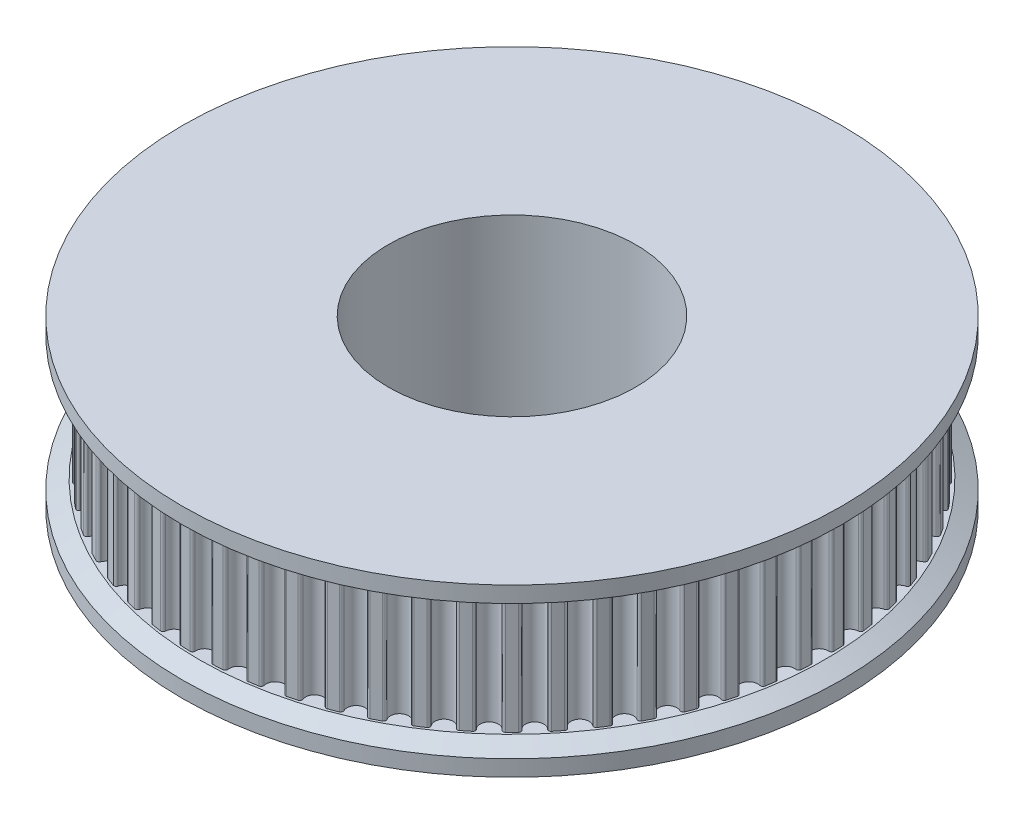
SolidWorks part; units mm, degrees
material "1060 Сплав"
ref_plane "Спереди" through (0, 0, 0) normal (0, 0, 1) x (1, 0, 0)
ref_plane "Сверху" through (0, 0, 0) normal (0, 1, 0) x (1, 0, 0)
ref_plane "Справа" through (0, 0, 0) normal (1, 0, 0) x (0, 0, -1)
other "Configuration Table"
sketch "Эскиз1" plane through (0, 0, 0) normal (0, 1, 0) x (1, 0, 0)
  circle A0 centre (0, 0) radius 10
  circle A1 centre (0, 0) radius 7.5
  dimension "D1" = 20
  dimension "D2" = 15
extrude "Бобышка-Вытянуть1" add sketch "Эскиз1" along normal blind 7.45
sketch "Эскиз2" plane through (0, 7.45, 0) normal (0, 1, 0) x (1, 0, 0)
  arc A1 (1.2682, 18.8073) -> (0.7046, 18.8368) centre (0, 0) ccw
  arc A3 (-0.5492, 18.679) -> (0.5492, 18.679) centre (0, 18.65) ccw
  arc A74 (-0.5492, 18.679) -> (-0.7046, 18.8368) centre (-0.699, 18.6869) ccw
  arc A77 (0.5492, 18.679) -> (0.7046, 18.8368) centre (0.699, 18.6869) cw
  arc A82 (-0.7046, 18.8368) -> (-1.2682, 18.8073) centre (0, 0) ccw
  arc A83 (1.4063, 18.6341) -> (2.4987, 18.5193) centre (1.9495, 18.5478) ccw
  arc A84 (1.4063, 18.6341) -> (1.2682, 18.8073) centre (1.2581, 18.6576) ccw
  arc A85 (2.4987, 18.5193) -> (2.6698, 18.66) centre (2.6485, 18.5115) cw
  arc A86 (3.3464, 18.385) -> (4.4208, 18.1566) centre (3.8776, 18.2425) ccw
  arc A87 (3.3464, 18.385) -> (3.2272, 18.5717) centre (3.2015, 18.4239) ccw
  arc A88 (4.4208, 18.1566) -> (4.6056, 18.2787) centre (4.569, 18.1332) cw
  arc A89 (5.2498, 17.9345) -> (6.2945, 17.5951) centre (5.7632, 17.7372) ccw
  arc A90 (5.2498, 17.9345) -> (5.1508, 18.1326) centre (5.1098, 17.9883) ccw
  arc A91 (6.2945, 17.5951) -> (6.491, 17.6971) centre (6.4394, 17.5563) cw
  arc A92 (7.0957, 17.2875) -> (8.0992, 16.8407) centre (7.5856, 17.0376) ccw
  arc A93 (7.0957, 17.2875) -> (7.0179, 17.4949) centre (6.9621, 17.3557) ccw
  arc A94 (8.0992, 16.8407) -> (8.3053, 16.9217) centre (8.2393, 16.787) cw
  arc A95 (8.8639, 16.4511) -> (9.8152, 15.9019) centre (9.325, 16.1514) ccw
  arc A96 (8.8639, 16.4511) -> (8.8082, 16.6655) centre (8.7381, 16.5329) ccw
  arc A97 (9.8152, 15.9019) -> (10.0286, 15.9609) centre (9.9488, 15.8338) cw
  arc A98 (10.5349, 15.4345) -> (11.4236, 14.7888) centre (10.9622, 15.0882) ccw
  arc A99 (10.5349, 15.4345) -> (10.5019, 15.6535) centre (10.4184, 15.5289) ccw
  arc A100 (11.4236, 14.7888) -> (11.6421, 14.8251) centre (11.5494, 14.7072) cw
  arc A101 (12.0905, 14.2487) -> (12.9069, 13.5137) centre (12.4793, 13.8597) ccw
  arc A102 (12.0905, 14.2487) -> (12.0807, 14.47) centre (11.9845, 14.3548) ccw
  arc A103 (12.9069, 13.5137) -> (13.1279, 13.527) centre (13.0235, 13.4194) cw
  arc A104 (13.5137, 12.9069) -> (14.2487, 12.0905) centre (13.8597, 12.4793) ccw
  arc A105 (13.5137, 12.9069) -> (13.527, 13.1279) centre (13.4194, 13.0235) ccw
  arc A106 (14.2487, 12.0905) -> (14.47, 12.0807) centre (14.3548, 11.9845) cw
  arc A107 (14.7888, 11.4236) -> (15.4345, 10.5349) centre (15.0882, 10.9622) ccw
  arc A108 (14.7888, 11.4236) -> (14.8251, 11.6421) centre (14.7072, 11.5494) ccw
  arc A109 (15.4345, 10.5349) -> (15.6535, 10.5019) centre (15.5289, 10.4184) cw
  arc A110 (15.9019, 9.8152) -> (16.4511, 8.8639) centre (16.1514, 9.325) ccw
  arc A111 (15.9019, 9.8152) -> (15.9609, 10.0286) centre (15.8338, 9.9488) ccw
  arc A112 (16.4511, 8.8639) -> (16.6655, 8.8082) centre (16.5329, 8.7381) cw
  arc A113 (16.8407, 8.0992) -> (17.2875, 7.0957) centre (17.0376, 7.5856) ccw
  arc A114 (16.8407, 8.0992) -> (16.9217, 8.3053) centre (16.787, 8.2393) ccw
  arc A115 (17.2875, 7.0957) -> (17.4949, 7.0179) centre (17.3557, 6.9621) cw
  arc A116 (17.5951, 6.2945) -> (17.9345, 5.2498) centre (17.7372, 5.7632) ccw
  arc A117 (17.5951, 6.2945) -> (17.6971, 6.491) centre (17.5563, 6.4394) ccw
  arc A118 (17.9345, 5.2498) -> (18.1326, 5.1508) centre (17.9883, 5.1098) cw
  arc A119 (18.1566, 4.4208) -> (18.385, 3.3464) centre (18.2425, 3.8776) ccw
  arc A120 (18.1566, 4.4208) -> (18.2787, 4.6056) centre (18.1332, 4.569) ccw
  arc A121 (18.385, 3.3464) -> (18.5717, 3.2272) centre (18.4239, 3.2015) cw
  arc A122 (18.5193, 2.4987) -> (18.6341, 1.4063) centre (18.5478, 1.9495) ccw
  arc A123 (18.5193, 2.4987) -> (18.66, 2.6698) centre (18.5115, 2.6485) ccw
  arc A124 (18.6341, 1.4063) -> (18.8073, 1.2682) centre (18.6576, 1.2581) cw
  arc A125 (18.679, 0.5492) -> (18.679, -0.5492) centre (18.65, 0) ccw
  arc A126 (18.679, 0.5492) -> (18.8368, 0.7046) centre (18.6869, 0.699) ccw
  arc A127 (18.679, -0.5492) -> (18.8368, -0.7046) centre (18.6869, -0.699) cw
  arc A128 (18.6341, -1.4063) -> (18.5193, -2.4987) centre (18.5478, -1.9495) ccw
  arc A129 (18.6341, -1.4063) -> (18.8073, -1.2682) centre (18.6576, -1.2581) ccw
  arc A130 (18.5193, -2.4987) -> (18.66, -2.6698) centre (18.5115, -2.6485) cw
  arc A131 (18.385, -3.3464) -> (18.1566, -4.4208) centre (18.2425, -3.8776) ccw
  arc A132 (18.385, -3.3464) -> (18.5717, -3.2272) centre (18.4239, -3.2015) ccw
  arc A133 (18.1566, -4.4208) -> (18.2787, -4.6056) centre (18.1332, -4.569) cw
  arc A134 (17.9345, -5.2498) -> (17.5951, -6.2945) centre (17.7372, -5.7632) ccw
  arc A135 (17.9345, -5.2498) -> (18.1326, -5.1508) centre (17.9883, -5.1098) ccw
  arc A136 (17.5951, -6.2945) -> (17.6971, -6.491) centre (17.5563, -6.4394) cw
  arc A137 (17.2875, -7.0957) -> (16.8407, -8.0992) centre (17.0376, -7.5856) ccw
  arc A138 (17.2875, -7.0957) -> (17.4949, -7.0179) centre (17.3557, -6.9621) ccw
  arc A139 (16.8407, -8.0992) -> (16.9217, -8.3053) centre (16.787, -8.2393) cw
  arc A140 (16.4511, -8.8639) -> (15.9019, -9.8152) centre (16.1514, -9.325) ccw
  arc A141 (16.4511, -8.8639) -> (16.6655, -8.8082) centre (16.5329, -8.7381) ccw
  arc A142 (15.9019, -9.8152) -> (15.9609, -10.0286) centre (15.8338, -9.9488) cw
  arc A143 (15.4345, -10.5349) -> (14.7888, -11.4236) centre (15.0882, -10.9622) ccw
  arc A144 (15.4345, -10.5349) -> (15.6535, -10.5019) centre (15.5289, -10.4184) ccw
  arc A145 (14.7888, -11.4236) -> (14.8251, -11.6421) centre (14.7072, -11.5494) cw
  arc A146 (14.2487, -12.0905) -> (13.5137, -12.9069) centre (13.8597, -12.4793) ccw
  arc A147 (14.2487, -12.0905) -> (14.47, -12.0807) centre (14.3548, -11.9845) ccw
  arc A148 (13.5137, -12.9069) -> (13.527, -13.1279) centre (13.4194, -13.0235) cw
  arc A149 (12.9069, -13.5137) -> (12.0905, -14.2487) centre (12.4793, -13.8597) ccw
  arc A150 (12.9069, -13.5137) -> (13.1279, -13.527) centre (13.0235, -13.4194) ccw
  arc A151 (12.0905, -14.2487) -> (12.0807, -14.47) centre (11.9845, -14.3548) cw
  arc A152 (11.4236, -14.7888) -> (10.5349, -15.4345) centre (10.9622, -15.0882) ccw
  arc A153 (11.4236, -14.7888) -> (11.6421, -14.8251) centre (11.5494, -14.7072) ccw
  arc A154 (10.5349, -15.4345) -> (10.5019, -15.6535) centre (10.4184, -15.5289) cw
  arc A155 (9.8152, -15.9019) -> (8.8639, -16.4511) centre (9.325, -16.1514) ccw
  arc A156 (9.8152, -15.9019) -> (10.0286, -15.9609) centre (9.9488, -15.8338) ccw
  arc A157 (8.8639, -16.4511) -> (8.8082, -16.6655) centre (8.7381, -16.5329) cw
  arc A158 (8.0992, -16.8407) -> (7.0957, -17.2875) centre (7.5856, -17.0376) ccw
  arc A159 (8.0992, -16.8407) -> (8.3053, -16.9217) centre (8.2393, -16.787) ccw
  arc A160 (7.0957, -17.2875) -> (7.0179, -17.4949) centre (6.9621, -17.3557) cw
  arc A161 (6.2945, -17.5951) -> (5.2498, -17.9345) centre (5.7632, -17.7372) ccw
  arc A162 (6.2945, -17.5951) -> (6.491, -17.6971) centre (6.4394, -17.5563) ccw
  arc A163 (5.2498, -17.9345) -> (5.1508, -18.1326) centre (5.1098, -17.9883) cw
  arc A164 (4.4208, -18.1566) -> (3.3464, -18.385) centre (3.8776, -18.2425) ccw
  arc A165 (4.4208, -18.1566) -> (4.6056, -18.2787) centre (4.569, -18.1332) ccw
  arc A166 (3.3464, -18.385) -> (3.2272, -18.5717) centre (3.2015, -18.4239) cw
  arc A167 (2.4987, -18.5193) -> (1.4063, -18.6341) centre (1.9495, -18.5478) ccw
  arc A168 (2.4987, -18.5193) -> (2.6698, -18.66) centre (2.6485, -18.5115) ccw
  arc A169 (1.4063, -18.6341) -> (1.2682, -18.8073) centre (1.2581, -18.6576) cw
  arc A170 (0.5492, -18.679) -> (-0.5492, -18.679) centre (0, -18.65) ccw
  arc A171 (0.5492, -18.679) -> (0.7046, -18.8368) centre (0.699, -18.6869) ccw
  arc A172 (-0.5492, -18.679) -> (-0.7046, -18.8368) centre (-0.699, -18.6869) cw
  arc A173 (-1.4063, -18.6341) -> (-2.4987, -18.5193) centre (-1.9495, -18.5478) ccw
  arc A174 (-1.4063, -18.6341) -> (-1.2682, -18.8073) centre (-1.2581, -18.6576) ccw
  arc A175 (-2.4987, -18.5193) -> (-2.6698, -18.66) centre (-2.6485, -18.5115) cw
  arc A176 (-3.3464, -18.385) -> (-4.4208, -18.1566) centre (-3.8776, -18.2425) ccw
  arc A177 (-3.3464, -18.385) -> (-3.2272, -18.5717) centre (-3.2015, -18.4239) ccw
  arc A178 (-4.4208, -18.1566) -> (-4.6056, -18.2787) centre (-4.569, -18.1332) cw
  arc A179 (-5.2498, -17.9345) -> (-6.2945, -17.5951) centre (-5.7632, -17.7372) ccw
  arc A180 (-5.2498, -17.9345) -> (-5.1508, -18.1326) centre (-5.1098, -17.9883) ccw
  arc A181 (-6.2945, -17.5951) -> (-6.491, -17.6971) centre (-6.4394, -17.5563) cw
  arc A182 (-7.0957, -17.2875) -> (-8.0992, -16.8407) centre (-7.5856, -17.0376) ccw
  arc A183 (-7.0957, -17.2875) -> (-7.0179, -17.4949) centre (-6.9621, -17.3557) ccw
  arc A184 (-8.0992, -16.8407) -> (-8.3053, -16.9217) centre (-8.2393, -16.787) cw
  arc A185 (-8.8639, -16.4511) -> (-9.8152, -15.9019) centre (-9.325, -16.1514) ccw
  arc A186 (-8.8639, -16.4511) -> (-8.8082, -16.6655) centre (-8.7381, -16.5329) ccw
  arc A187 (-9.8152, -15.9019) -> (-10.0286, -15.9609) centre (-9.9488, -15.8338) cw
  arc A188 (-10.5349, -15.4345) -> (-11.4236, -14.7888) centre (-10.9622, -15.0882) ccw
  arc A189 (-10.5349, -15.4345) -> (-10.5019, -15.6535) centre (-10.4184, -15.5289) ccw
  arc A190 (-11.4236, -14.7888) -> (-11.6421, -14.8251) centre (-11.5494, -14.7072) cw
  arc A191 (-12.0905, -14.2487) -> (-12.9069, -13.5137) centre (-12.4793, -13.8597) ccw
  arc A192 (-12.0905, -14.2487) -> (-12.0807, -14.47) centre (-11.9845, -14.3548) ccw
  arc A193 (-12.9069, -13.5137) -> (-13.1279, -13.527) centre (-13.0235, -13.4194) cw
  arc A194 (-13.5137, -12.9069) -> (-14.2487, -12.0905) centre (-13.8597, -12.4793) ccw
  arc A195 (-13.5137, -12.9069) -> (-13.527, -13.1279) centre (-13.4194, -13.0235) ccw
  arc A196 (-14.2487, -12.0905) -> (-14.47, -12.0807) centre (-14.3548, -11.9845) cw
  arc A197 (-14.7888, -11.4236) -> (-15.4345, -10.5349) centre (-15.0882, -10.9622) ccw
  arc A198 (-14.7888, -11.4236) -> (-14.8251, -11.6421) centre (-14.7072, -11.5494) ccw
  arc A199 (-15.4345, -10.5349) -> (-15.6535, -10.5019) centre (-15.5289, -10.4184) cw
  arc A200 (-15.9019, -9.8152) -> (-16.4511, -8.8639) centre (-16.1514, -9.325) ccw
  arc A201 (-15.9019, -9.8152) -> (-15.9609, -10.0286) centre (-15.8338, -9.9488) ccw
  arc A202 (-16.4511, -8.8639) -> (-16.6655, -8.8082) centre (-16.5329, -8.7381) cw
  arc A203 (-16.8407, -8.0992) -> (-17.2875, -7.0957) centre (-17.0376, -7.5856) ccw
  arc A204 (-16.8407, -8.0992) -> (-16.9217, -8.3053) centre (-16.787, -8.2393) ccw
  arc A205 (-17.2875, -7.0957) -> (-17.4949, -7.0179) centre (-17.3557, -6.9621) cw
  arc A206 (-17.5951, -6.2945) -> (-17.9345, -5.2498) centre (-17.7372, -5.7632) ccw
  arc A207 (-17.5951, -6.2945) -> (-17.6971, -6.491) centre (-17.5563, -6.4394) ccw
  arc A208 (-17.9345, -5.2498) -> (-18.1326, -5.1508) centre (-17.9883, -5.1098) cw
  arc A209 (-18.1566, -4.4208) -> (-18.385, -3.3464) centre (-18.2425, -3.8776) ccw
  arc A210 (-18.1566, -4.4208) -> (-18.2787, -4.6056) centre (-18.1332, -4.569) ccw
  arc A211 (-18.385, -3.3464) -> (-18.5717, -3.2272) centre (-18.4239, -3.2015) cw
  arc A212 (-18.5193, -2.4987) -> (-18.6341, -1.4063) centre (-18.5478, -1.9495) ccw
  arc A213 (-18.5193, -2.4987) -> (-18.66, -2.6698) centre (-18.5115, -2.6485) ccw
  arc A214 (-18.6341, -1.4063) -> (-18.8073, -1.2682) centre (-18.6576, -1.2581) cw
  arc A215 (-18.679, -0.5492) -> (-18.679, 0.5492) centre (-18.65, 0) ccw
  arc A216 (-18.679, -0.5492) -> (-18.8368, -0.7046) centre (-18.6869, -0.699) ccw
  arc A217 (-18.679, 0.5492) -> (-18.8368, 0.7046) centre (-18.6869, 0.699) cw
  arc A218 (-18.6341, 1.4063) -> (-18.5193, 2.4987) centre (-18.5478, 1.9495) ccw
  arc A219 (-18.6341, 1.4063) -> (-18.8073, 1.2682) centre (-18.6576, 1.2581) ccw
  arc A220 (-18.5193, 2.4987) -> (-18.66, 2.6698) centre (-18.5115, 2.6485) cw
  arc A221 (-18.385, 3.3464) -> (-18.1566, 4.4208) centre (-18.2425, 3.8776) ccw
  arc A222 (-18.385, 3.3464) -> (-18.5717, 3.2272) centre (-18.4239, 3.2015) ccw
  arc A223 (-18.1566, 4.4208) -> (-18.2787, 4.6056) centre (-18.1332, 4.569) cw
  arc A224 (-17.9345, 5.2498) -> (-17.5951, 6.2945) centre (-17.7372, 5.7632) ccw
  arc A225 (-17.9345, 5.2498) -> (-18.1326, 5.1508) centre (-17.9883, 5.1098) ccw
  arc A226 (-17.5951, 6.2945) -> (-17.6971, 6.491) centre (-17.5563, 6.4394) cw
  arc A227 (-17.2875, 7.0957) -> (-16.8407, 8.0992) centre (-17.0376, 7.5856) ccw
  arc A228 (-17.2875, 7.0957) -> (-17.4949, 7.0179) centre (-17.3557, 6.9621) ccw
  arc A229 (-16.8407, 8.0992) -> (-16.9217, 8.3053) centre (-16.787, 8.2393) cw
  arc A230 (-16.4511, 8.8639) -> (-15.9019, 9.8152) centre (-16.1514, 9.325) ccw
  arc A231 (-16.4511, 8.8639) -> (-16.6655, 8.8082) centre (-16.5329, 8.7381) ccw
  arc A232 (-15.9019, 9.8152) -> (-15.9609, 10.0286) centre (-15.8338, 9.9488) cw
  arc A233 (-15.4345, 10.5349) -> (-14.7888, 11.4236) centre (-15.0882, 10.9622) ccw
  arc A234 (-15.4345, 10.5349) -> (-15.6535, 10.5019) centre (-15.5289, 10.4184) ccw
  arc A235 (-14.7888, 11.4236) -> (-14.8251, 11.6421) centre (-14.7072, 11.5494) cw
  arc A236 (-14.2487, 12.0905) -> (-13.5137, 12.9069) centre (-13.8597, 12.4793) ccw
  arc A237 (-14.2487, 12.0905) -> (-14.47, 12.0807) centre (-14.3548, 11.9845) ccw
  arc A238 (-13.5137, 12.9069) -> (-13.527, 13.1279) centre (-13.4194, 13.0235) cw
  arc A239 (-12.9069, 13.5137) -> (-12.0905, 14.2487) centre (-12.4793, 13.8597) ccw
  arc A240 (-12.9069, 13.5137) -> (-13.1279, 13.527) centre (-13.0235, 13.4194) ccw
  arc A241 (-12.0905, 14.2487) -> (-12.0807, 14.47) centre (-11.9845, 14.3548) cw
  arc A242 (-11.4236, 14.7888) -> (-10.5349, 15.4345) centre (-10.9622, 15.0882) ccw
  arc A243 (-11.4236, 14.7888) -> (-11.6421, 14.8251) centre (-11.5494, 14.7072) ccw
  arc A244 (-10.5349, 15.4345) -> (-10.5019, 15.6535) centre (-10.4184, 15.5289) cw
  arc A245 (-9.8152, 15.9019) -> (-8.8639, 16.4511) centre (-9.325, 16.1514) ccw
  arc A246 (-9.8152, 15.9019) -> (-10.0286, 15.9609) centre (-9.9488, 15.8338) ccw
  arc A247 (-8.8639, 16.4511) -> (-8.8082, 16.6655) centre (-8.7381, 16.5329) cw
  arc A248 (-8.0992, 16.8407) -> (-7.0957, 17.2875) centre (-7.5856, 17.0376) ccw
  arc A249 (-8.0992, 16.8407) -> (-8.3053, 16.9217) centre (-8.2393, 16.787) ccw
  arc A250 (-7.0957, 17.2875) -> (-7.0179, 17.4949) centre (-6.9621, 17.3557) cw
  arc A251 (-6.2945, 17.5951) -> (-5.2498, 17.9345) centre (-5.7632, 17.7372) ccw
  arc A252 (-6.2945, 17.5951) -> (-6.491, 17.6971) centre (-6.4394, 17.5563) ccw
  arc A253 (-5.2498, 17.9345) -> (-5.1508, 18.1326) centre (-5.1098, 17.9883) cw
  arc A254 (-4.4208, 18.1566) -> (-3.3464, 18.385) centre (-3.8776, 18.2425) ccw
  arc A255 (-4.4208, 18.1566) -> (-4.6056, 18.2787) centre (-4.569, 18.1332) ccw
  arc A256 (-3.3464, 18.385) -> (-3.2272, 18.5717) centre (-3.2015, 18.4239) cw
  arc A257 (-2.4987, 18.5193) -> (-1.4063, 18.6341) centre (-1.9495, 18.5478) ccw
  arc A258 (-2.4987, 18.5193) -> (-2.6698, 18.66) centre (-2.6485, 18.5115) ccw
  arc A259 (-1.4063, 18.6341) -> (-1.2682, 18.8073) centre (-1.2581, 18.6576) cw
  arc A260 (3.2272, 18.5717) -> (2.6698, 18.66) centre (0, 0) ccw
  arc A261 (5.1508, 18.1326) -> (4.6056, 18.2787) centre (0, 0) ccw
  arc A262 (7.0179, 17.4949) -> (6.491, 17.6971) centre (0, 0) ccw
  arc A263 (8.8082, 16.6655) -> (8.3053, 16.9217) centre (0, 0) ccw
  arc A264 (10.5019, 15.6535) -> (10.0286, 15.9609) centre (0, 0) ccw
  arc A265 (12.0807, 14.47) -> (11.6421, 14.8251) centre (0, 0) ccw
  arc A266 (13.527, 13.1279) -> (13.1279, 13.527) centre (0, 0) ccw
  arc A267 (14.8251, 11.6421) -> (14.47, 12.0807) centre (0, 0) ccw
  arc A268 (15.9609, 10.0286) -> (15.6535, 10.5019) centre (0, 0) ccw
  arc A269 (16.9217, 8.3053) -> (16.6655, 8.8082) centre (0, 0) ccw
  arc A270 (18.5717, -3.2272) -> (18.66, -2.6698) centre (0, 0) ccw
  arc A271 (18.8073, -1.2682) -> (18.8368, -0.7046) centre (0, 0) ccw
  arc A272 (18.8368, 0.7046) -> (18.8073, 1.2682) centre (0, 0) ccw
  arc A273 (18.66, 2.6698) -> (18.5717, 3.2272) centre (0, 0) ccw
  arc A274 (18.2787, 4.6056) -> (18.1326, 5.1508) centre (0, 0) ccw
  arc A275 (17.6971, 6.491) -> (17.4949, 7.0179) centre (0, 0) ccw
  arc A276 (14.47, -12.0807) -> (14.8251, -11.6421) centre (0, 0) ccw
  arc A277 (15.6535, -10.5019) -> (15.9609, -10.0286) centre (0, 0) ccw
  arc A278 (16.6655, -8.8082) -> (16.9217, -8.3053) centre (0, 0) ccw
  arc A279 (17.4949, -7.0179) -> (17.6971, -6.491) centre (0, 0) ccw
  arc A280 (18.1326, -5.1508) -> (18.2787, -4.6056) centre (0, 0) ccw
  arc A281 (2.6698, -18.66) -> (3.2272, -18.5717) centre (0, 0) ccw
  arc A282 (4.6056, -18.2787) -> (5.1508, -18.1326) centre (0, 0) ccw
  arc A283 (6.491, -17.6971) -> (7.0179, -17.4949) centre (0, 0) ccw
  arc A284 (8.3053, -16.9217) -> (8.8082, -16.6655) centre (0, 0) ccw
  arc A285 (10.0286, -15.9609) -> (10.5019, -15.6535) centre (0, 0) ccw
  arc A286 (11.6421, -14.8251) -> (12.0807, -14.47) centre (0, 0) ccw
  arc A287 (13.1279, -13.527) -> (13.527, -13.1279) centre (0, 0) ccw
  arc A288 (-7.0179, -17.4949) -> (-6.491, -17.6971) centre (0, 0) ccw
  arc A289 (-5.1508, -18.1326) -> (-4.6056, -18.2787) centre (0, 0) ccw
  arc A290 (-3.2272, -18.5717) -> (-2.6698, -18.66) centre (0, 0) ccw
  arc A291 (-1.2682, -18.8073) -> (-0.7046, -18.8368) centre (0, 0) ccw
  arc A292 (0.7046, -18.8368) -> (1.2682, -18.8073) centre (0, 0) ccw
  arc A293 (-16.9217, -8.3053) -> (-16.6655, -8.8082) centre (0, 0) ccw
  arc A294 (-15.9609, -10.0286) -> (-15.6535, -10.5019) centre (0, 0) ccw
  arc A295 (-14.8251, -11.6421) -> (-14.47, -12.0807) centre (0, 0) ccw
  arc A296 (-13.527, -13.1279) -> (-13.1279, -13.527) centre (0, 0) ccw
  arc A297 (-12.0807, -14.47) -> (-11.6421, -14.8251) centre (0, 0) ccw
  arc A298 (-10.5019, -15.6535) -> (-10.0286, -15.9609) centre (0, 0) ccw
  arc A299 (-8.8082, -16.6655) -> (-8.3053, -16.9217) centre (0, 0) ccw
  arc A300 (-17.6971, -6.491) -> (-17.4949, -7.0179) centre (0, 0) ccw
  arc A301 (-18.2787, -4.6056) -> (-18.1326, -5.1508) centre (0, 0) ccw
  arc A302 (-18.66, -2.6698) -> (-18.5717, -3.2272) centre (0, 0) ccw
  arc A303 (-18.8368, -0.7046) -> (-18.8073, -1.2682) centre (0, 0) ccw
  arc A304 (-18.8073, 1.2682) -> (-18.8368, 0.7046) centre (0, 0) ccw
  arc A305 (-18.5717, 3.2272) -> (-18.66, 2.6698) centre (0, 0) ccw
  arc A306 (-18.1326, 5.1508) -> (-18.2787, 4.6056) centre (0, 0) ccw
  arc A307 (-17.4949, 7.0179) -> (-17.6971, 6.491) centre (0, 0) ccw
  arc A308 (-16.6655, 8.8082) -> (-16.9217, 8.3053) centre (0, 0) ccw
  arc A309 (-15.6535, 10.5019) -> (-15.9609, 10.0286) centre (0, 0) ccw
  arc A310 (-14.47, 12.0807) -> (-14.8251, 11.6421) centre (0, 0) ccw
  arc A311 (-13.1279, 13.527) -> (-13.527, 13.1279) centre (0, 0) ccw
  arc A312 (-11.6421, 14.8251) -> (-12.0807, 14.47) centre (0, 0) ccw
  arc A313 (-10.0286, 15.9609) -> (-10.5019, 15.6535) centre (0, 0) ccw
  arc A314 (-8.3053, 16.9217) -> (-8.8082, 16.6655) centre (0, 0) ccw
  arc A315 (-6.491, 17.6971) -> (-7.0179, 17.4949) centre (0, 0) ccw
  arc A316 (-4.6056, 18.2787) -> (-5.1508, 18.1326) centre (0, 0) ccw
  arc A317 (-2.6698, 18.66) -> (-3.2272, 18.5717) centre (0, 0) ccw
  circle A318 centre (0, 0) radius 7.5 construction
  circle A319 centre (0, 0) radius 7.5
  point P426 (0, 0)
  dimension "D1" = 37.7
  dimension "D2" = 0.2
  dimension "D3" = 0.55
  dimension "D4" = 0.15
extrude "Бобышка-Вытянуть2" add sketch "Эскиз2" along normal blind 7
sketch "Эскиз3" plane through (0, 14.45, 0) normal (0, 1, 0) x (1, 0, 0)
  circle A3 centre (0, 0) radius 20
  circle A4 centre (0, 0) radius 7.5 construction
  circle A5 centre (0, 0) radius 7.5
  dimension "D1" = 40
extrude "Бобышка-Вытянуть3" add sketch "Эскиз3" along normal blind 1.55
sketch "Эскиз4" plane through (0, 0, 0) normal (0, 0, 1) x (1, 0, 0)
  line L0 (-10, 3.725) -> (10, 3.725) construction
  line L1 (-10, 7.45) -> (-10, 0) construction
  line L2 (10, 0) -> (10, 7.45) construction
  circle A0 centre (0, 3.725) radius 1.5
  dimension "D1" = 3
extrude "Вырез-Вытянуть1" cut sketch "Эскиз4" along normal up to surface (9.8869 mm away)
sketch "Эскиз7" plane through (0, 7.45, 0) normal (0, -1, 0) x (1, 0, 0)
  circle A0 centre (0, 0) radius 20 construction
  circle A1 centre (0, 0) radius 20
  circle A2 centre (0, 0) radius 7.5 construction
  circle A3 centre (0, 0) radius 7.5
extrude "Бобышка-Вытянуть4" add sketch "Эскиз7" along normal blind 1.55
sketch "Эскиз5" plane through (0, 0, 0) normal (1, 0, 0) x (0, 0, -1)
  line L0 (10, 2.95) -> (-9.9172, 2.95) construction
  line L1 (10, 0) -> (10, 5.9) construction
  circle A0 centre (0, 2.95) radius 1.5
  spline S1 degree 2 poles (-10, 5.225) (-9.775, 3.725) (-10, 2.225) knots 0 0 0 1 1 1 weights 0.0085 0.01 0.0115 construction
  dimension "D1" = 3
extrude "Вырез-Вытянуть2" cut sketch "Эскиз5" along normal up to surface (9.8869 mm away)
sketch "Эскиз6" plane through (0, 7.45, 0) normal (0, 1, 0) x (1, 0, 0)
  circle A0 centre (0, 0) radius 18.1
  arc A3 (-16.9217, -8.3053) -> (-16.6655, -8.8082) centre (0, 0) ccw construction
  dimension "D1" = 0.75
  dimension "D2" = 36.2
chamfer "Фаска1" distance 1 angle 30 2 edges at (0, 14.45, 20) (0, 7.45, -20)
sketch "Sketch1" plane through (0, 16, 0) normal (0, 1, 0) x (1, 0, 0)
  circle A0 centre (0, 0) radius 19 construction
  dimension "D1" = 38
